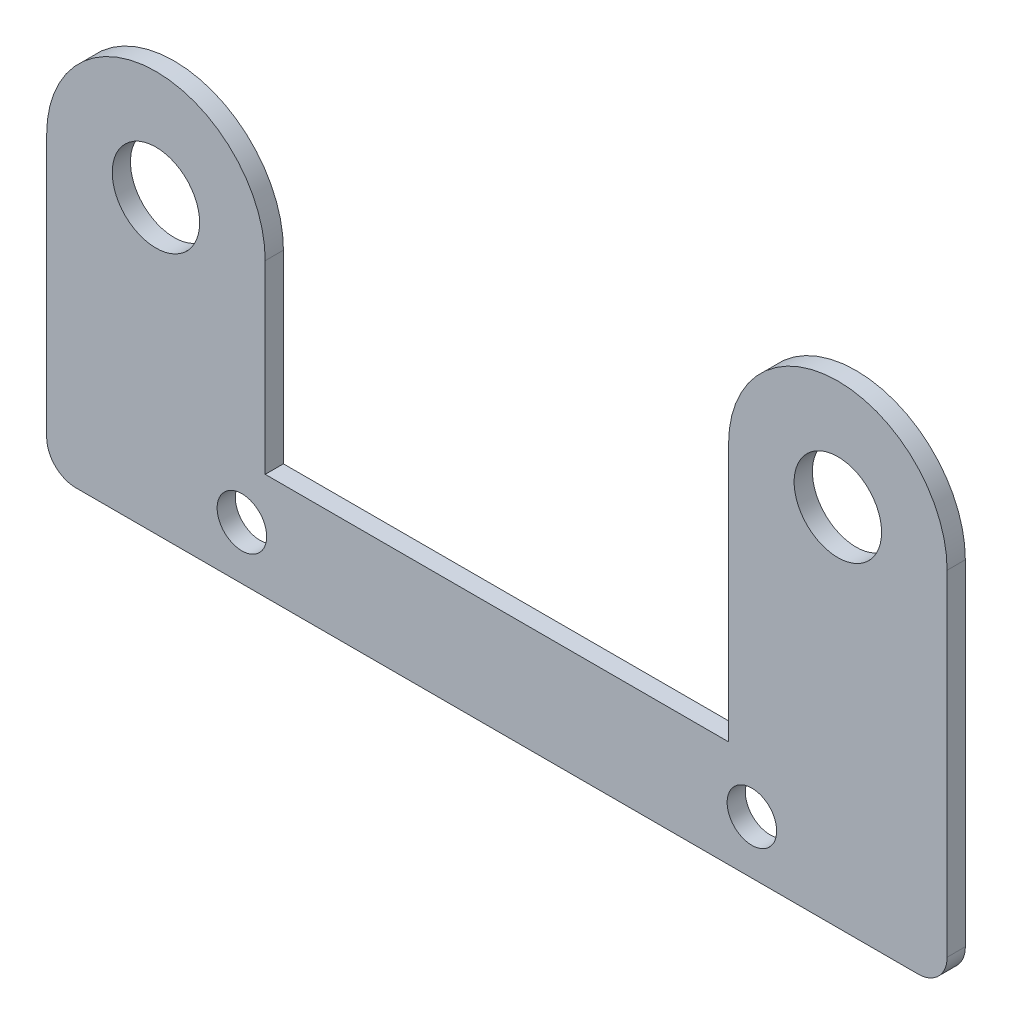
SolidWorks part; units mm, degrees
ref_plane "Front Plane" through (0, 0, 0) normal (0, 0, 1) x (1, 0, 0)
ref_plane "Top Plane" through (0, 0, 0) normal (0, 1, 0) x (1, 0, 0)
ref_plane "Right Plane" through (0, 0, 0) normal (1, 0, 0) x (0, 0, -1)
sketch "Sketch1" plane through (0, 0, 0) normal (0, 0, 1) x (1, 0, 0)
  line L0 (0, 25.4) -> (19.05, 25.4) construction
  line L2 (0, 25.4) -> (0, 0)
  line L3 (0, 0) -> (78.486, 0)
  line L4 (78.486, 31.75) -> (78.486, 0)
  line L5 (19.05, 25.4) -> (19.05, 9.271)
  line L6 (19.05, 9.271) -> (59.436, 9.271)
  line L7 (59.436, 9.271) -> (59.436, 31.75)
  line L8 (59.436, 31.75) -> (78.486, 31.75) construction
  line L10 (17.018, 4.6355) -> (61.468, 4.6355) construction
  line L11 (39.243, 9.271) -> (39.243, 0) construction
  circle A0 centre (17.018, 4.6355) radius 2.159
  circle A1 centre (61.468, 4.6355) radius 2.159
  circle A2 centre (9.525, 25.4) radius 3.81
  circle A3 centre (68.961, 31.75) radius 3.81
  arc A4 (0, 25.4) -> (19.05, 25.4) centre (9.525, 25.4) cw
  arc A5 (59.436, 31.75) -> (78.486, 31.75) centre (68.961, 31.75) cw
  point P0 (39.243, 4.6355)
  point P3 (59.436, 9.271)
  point P6 (0, 0)
  point P9 (19.05, 9.271)
  point P22 (19.05, 9.271)
  point P23 (59.436, 9.271)
  point P24 (17.018, 4.6355)
  dimension "D1" = 4.318
  dimension "D5" = 7.62
  dimension "D2" = 44.45
  dimension "D3" = 78.486
  dimension "D4" = 9.271
  dimension "D6" = 25.4
  dimension "D7" = 31.75
  dimension "D8" = 19.05
extrude "Boss-Extrude1" add sketch "Sketch1" along normal blind 1.5875
fillet "Fillet1" radius 2.54 2 edges at (78.486, 0, 0.7937) (0, 0, 0.7937)
